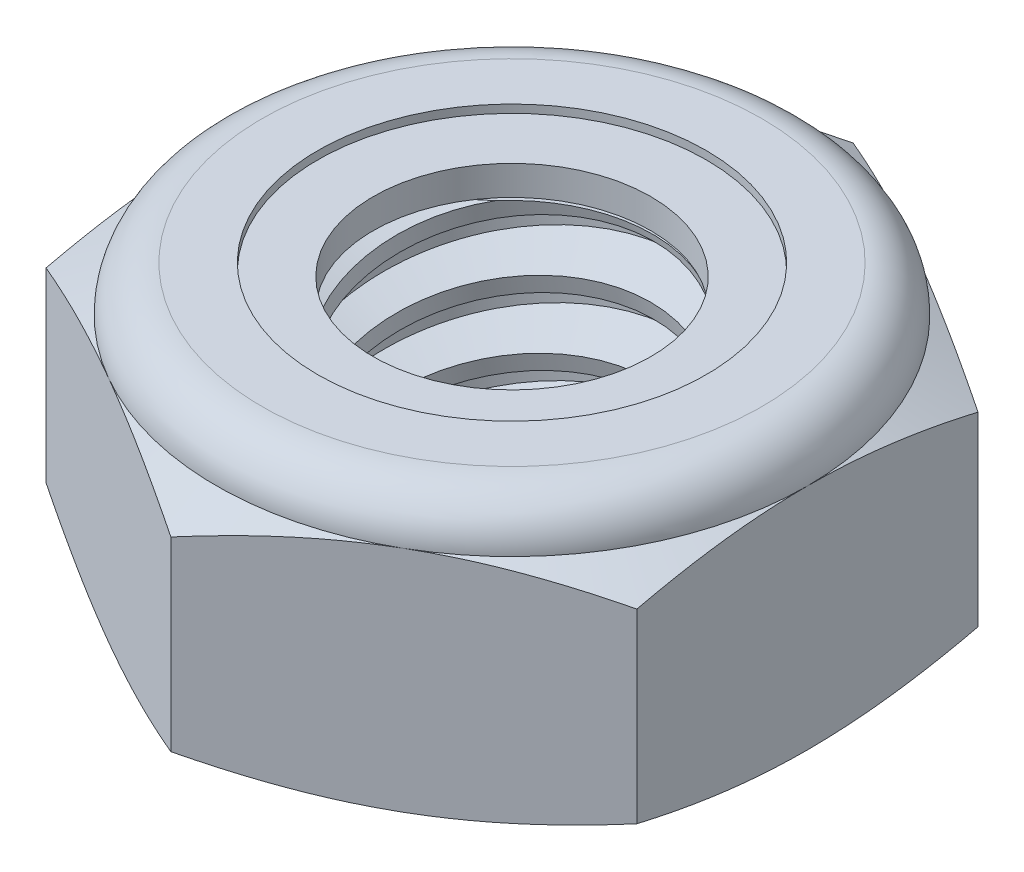
SolidWorks part; units mm, degrees
ref_plane "Front" through (0, 0, 0) normal (0, 0, 1) x (1, 0, 0)
ref_plane "Top" through (0, 0, 0) normal (0, 1, 0) x (1, 0, 0)
ref_plane "Right" through (0, 0, 0) normal (1, 0, 0) x (0, 0, -1)
sketch "Sketch1" plane through (0, 0, 0) normal (0, 1, 0) x (1, 0, 0)
  line L1 (0, 6.4158) -> (-5.5563, 3.2079)
  line L2 (-5.5563, 3.2079) -> (-5.5563, -3.2079)
  line L3 (-5.5563, -3.2079) -> (0, -6.4158)
  line L4 (0, -6.4158) -> (5.5562, -3.2079)
  line L5 (5.5562, -3.2079) -> (5.5562, 3.2079)
  line L6 (5.5562, 3.2079) -> (0, 6.4158)
  circle A0 centre (0, 0) radius 5.5563 construction
  dimension "Hex Flats" = 11.1125
extrude "Extrude1" add sketch "Sketch1" along normal blind 5.1594
sketch "Sketch2" plane through (0, 0, 0) normal (1, 0, 0) x (0, 0, -1)
  line L0 (-3.175, 0) -> (-3.175, 5.1594) construction
  line L1 (0, 0) -> (3.175, 0)
  line L2 (0, 0) -> (0, 5.1594)
  line L3 (0, 5.1594) -> (3.175, 5.1594)
  line L4 (3.175, 0) -> (3.175, 5.1594)
  line L5 (-3.2079, 5.1594) -> (3.2079, 5.1594) construction
  line L7 (0, -3.175) -> (0, 0) construction
  dimension "Thread Dia" = 6.35
revolve "Revolve1" add sketch "Sketch2" angle 360 about L7
sketch "Sketch3" plane through (0, 0, 0) normal (1, 0, 0) x (0, 0, -1)
  line L0 (3.175, 5.1594) -> (-3.175, 5.1594) construction
  line L1 (-3.175, 5.1594) -> (-3.175, 3.8894) construction
  line L2 (-3.175, 3.8894) -> (3.175, 5.1594) construction
  line L3 (3.175, 5.1594) -> (3.2061, 5.0037) construction
  line L4 (3.2061, 5.0037) -> (3.4241, 3.914)
  line L5 (3.4241, 3.914) -> (2.6722, 4.1684)
  line L6 (2.6722, 4.1684) -> (2.6099, 4.4797)
  line L7 (2.6099, 4.4797) -> (3.2061, 5.0037)
  line L8 (2.641, 4.3241) -> (3.3151, 4.4589) construction
  line L9 (3.175, 5.1594) -> (3.175, 4.4309) construction
  line L10 (3.175, 4.4309) -> (-3.175, 3.1609) construction
  line L11 (-3.175, 3.1609) -> (-3.175, 3.8894) construction
  line L12 (-0.2727, 5.1594) -> (0.2727, 2.4323) construction
  line L13 (-3.175, 0) -> (-3.175, 5.1594) construction
  line L14 (0, 5.1594) -> (3.175, 5.1594) construction
  line L15 (3.175, 0) -> (3.175, 5.1594) construction
  point P13 (0, 3.7959)
  dimension "D1" = 0.1588
  dimension "D2" = 0.3175
  dimension "Thread Pitch" = 1.27
  dimension "D4" = 60
  dimension "D5" = 1.27
revolve "Cut-Revolve1" cut sketch "Sketch3" angle 360 about L12
pattern_linear "LPattern1" count 4 spacing 1.27 along (0, -1, 0) count 2 spacing 1.27 along (0, 1, 0) of "Cut-Revolve1"
sketch "Sketch4" plane through (0, 0, 0) normal (1, 0, 0) x (0, 0, -1)
  line L0 (0, 5.1594) -> (3.175, 5.1594)
  line L1 (3.175, 5.1594) -> (2.6099, 4.8959)
  line L2 (2.6099, 4.8959) -> (2.6099, 0.2635)
  line L3 (2.6099, 0.2635) -> (3.175, 0)
  line L4 (3.175, 0) -> (0, 0)
  line L5 (0, 0) -> (0, 5.1594)
  line L6 (3.175, 0) -> (3.175, 5.1594) construction
  line L7 (0, 5.1594) -> (3.175, 5.1594) construction
  line L8 (0, 0) -> (3.175, 0) construction
  line L9 (0, 0) -> (0, 5.1594) construction
  line L10 (0, 5.1594) -> (0, 5.7829) construction
  dimension "D1" = 25
revolve "Cut-Revolve2" cut sketch "Sketch4" angle 360 about L10
combine bodies "Combine1" operation type subtract main body 112 bodies to subtract 111
sketch "Sketch5" plane through (0, 0, 0) normal (1, 0, 0) x (0, 0, -1)
  line L0 (0, 0) -> (5.5563, 0)
  line L1 (5.5563, 0) -> (6.4158, 0.4008)
  line L2 (6.4158, 0.4008) -> (6.4158, 3.8987)
  line L3 (6.4158, 3.8987) -> (5.5563, 4.2995)
  line L4 (4.6964, 5.1594) -> (4.6964, 6.4294)
  line L5 (4.6964, 6.4294) -> (7.6858, 6.4294)
  line L6 (7.6858, 6.4294) -> (7.6858, -1.27)
  line L7 (7.6858, -1.27) -> (0, -1.27)
  line L8 (0, -1.27) -> (0, 0)
  line L9 (5.5563, 4.2995) -> (5.5563, 0) construction
  line L10 (0, 0) -> (3.175, 0) construction
  line L13 (6.4158, 2.1497) -> (7.6858, 2.1497) construction
  line L14 (6.4158, 5.1594) -> (6.4158, 0) construction
  line L15 (0, 0) -> (0, 6.4294) construction
  line L20 (0, 6.4294) -> (4.6964, 6.4294) construction
  line L22 (0, 5.1594) -> (3.175, 5.1594) construction
  arc A0 (5.5563, 4.2995) -> (4.6964, 5.1594) centre (4.6964, 4.2995) ccw
  dimension "D1" = 25
  dimension "D2" = 1.27
  dimension "D3" = 5.1594
  dimension "D4" = 0.8599
revolve "Cut-Revolve3" cut sketch "Sketch5" angle 360 about L15
sketch "Sketch6" plane through (0, 0, 0) normal (1, 0, 0) x (0, 0, -1)
  line L0 (0, 4.2995) -> (5.4039, 4.2995)
  line L1 (4.6964, 5.007) -> (3.6531, 5.007)
  line L2 (0, 6.4294) -> (0, 4.2995)
  line L3 (3.6531, 6.4294) -> (0, 6.4294)
  line L4 (0, 6.4294) -> (4.6964, 6.4294) construction
  line L5 (0, 0) -> (0, 6.4294) construction
  line L6 (0, 6.4294) -> (0, 44.323) construction
  line L7 (3.6531, 5.007) -> (3.6531, 6.4294)
  line L8 (4.6964, 5.1594) -> (4.6964, 5.007) construction
  line L9 (3.6531, 5.007) -> (2.6099, 5.007) construction
  line L10 (2.6099, 5.007) -> (2.6099, 4.8959) construction
  arc A0 (5.4039, 4.2995) -> (4.6964, 5.007) centre (4.6964, 4.2995) ccw
  arc A1 (5.5563, 4.2995) -> (4.6964, 5.1594) centre (4.6964, 4.2995) ccw construction
  dimension "D1" = 0.1524
revolve "Cut-Revolve4" cut sketch "Sketch6" angle 360 about L6
sketch "Sketch7" plane through (0, 0, 0) normal (1, 0, 0) x (0, 0, -1)
  line L0 (2.6099, 4.3757) -> (5.323, 4.3757)
  line L1 (4.6964, 4.9308) -> (2.6099, 4.9308)
  line L2 (2.6099, 4.9308) -> (2.6099, 4.3757)
  line L3 (2.6099, 4.3757) -> (0, 4.3757) construction
  line L4 (0, 4.3757) -> (0, 4.9308) construction
  line L5 (0, 4.9308) -> (2.6099, 4.9308) construction
  line L6 (2.6099, 4.3757) -> (2.6099, 4.2995) construction
  line L7 (0, 4.2995) -> (5.4039, 4.2995) construction
  line L8 (4.6964, 4.9308) -> (4.6964, 5.007) construction
  arc A0 (5.323, 4.3757) -> (4.6964, 4.9308) centre (4.6964, 4.2995) ccw
  arc A2 (5.4039, 4.2995) -> (4.6964, 5.007) centre (4.6964, 4.2995) ccw construction
  dimension "D1" = 0.0762
revolve "Revolve2" add sketch "Sketch7" angle 360 about L4
move or copy body "Body-Move/Copy1" [suppressed] bodies to move or copy 115 116
equation "\"D1@Sketch3\"=\"Thread Pitch@Sketch3\"/8"
equation "\"D2@Sketch3\"=\"Thread Pitch@Sketch3\"/4"
equation "\"D5@Sketch3\"=\"Thread Pitch@Sketch3\""
equation "\"D4@LPattern1\"=\"Thread Pitch@Sketch3\""
equation "\"D3@LPattern1\"=\"Thread Pitch@Sketch3\""
equation "\"D1@LPattern1\"=\"Height@Extrude1\"/\"Thread Pitch@Sketch3\""
equation "\"D4@Sketch5\"=\"Height@Extrude1\"/6"
